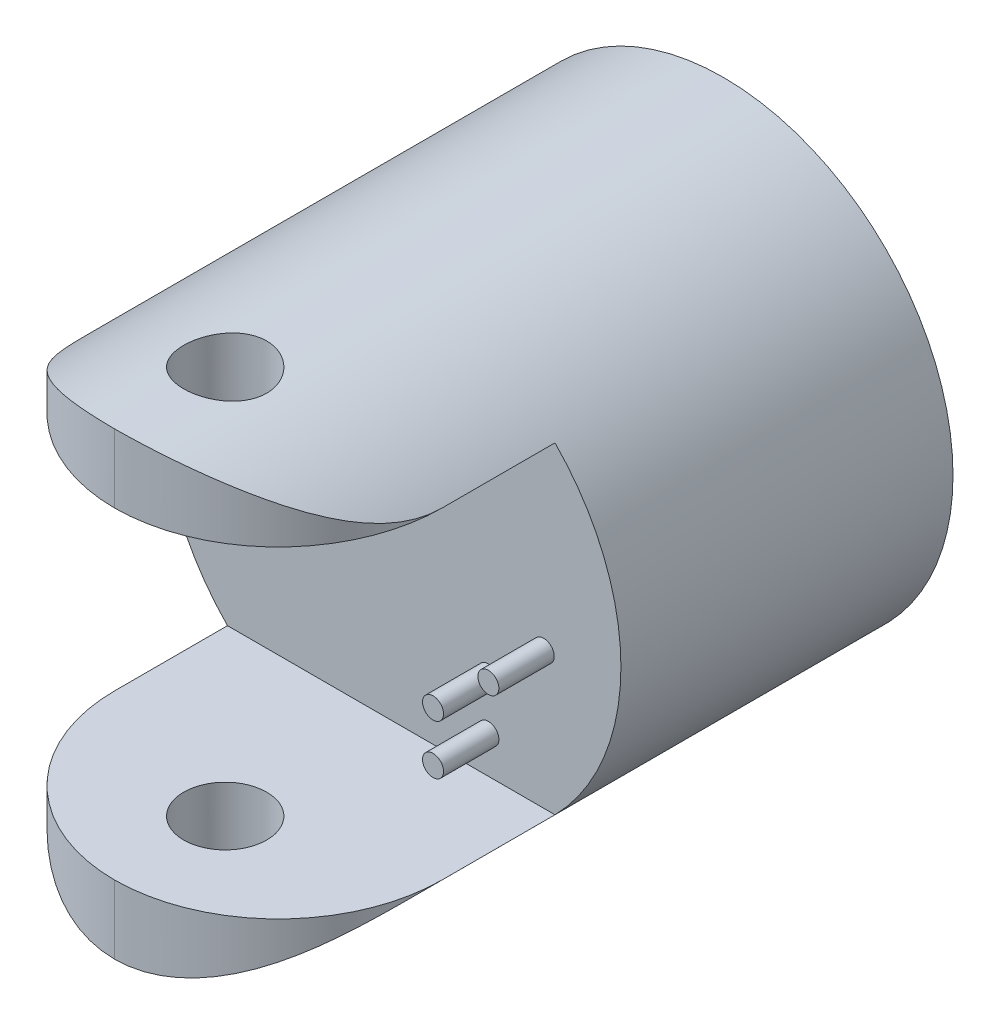
SolidWorks part; units mm, degrees
ref_plane "Front Plane" through (0, 0, 0) normal (0, 0, 1) x (1, 0, 0)
ref_plane "Top Plane" through (0, 0, 0) normal (0, 1, 0) x (1, 0, 0)
ref_plane "Right Plane" through (0, 0, 0) normal (1, 0, 0) x (0, 0, -1)
sketch "Sketch1" plane through (0, 0, 0) normal (0, 0, 1) x (1, 0, 0)
  circle A0 centre (0, 0) radius 4.15
extrude "Boss-Extrude1" add sketch "Sketch1" along normal blind 11
sketch "Sketch2" plane through (0, 0, 11) normal (0, 0, 1) x (1, 0, 0)
  line L1 (-4.1876, 2.91) -> (4.1876, 2.91)
  line L2 (-4.1876, 2.91) -> (-4.1876, -2.91)
  line L3 (-4.1876, -2.91) -> (4.1876, -2.91)
  line L4 (4.1876, 2.91) -> (4.1876, -2.91)
  line L5 (-4.1876, 2.91) -> (4.1876, -2.91) construction
  line L6 (-4.1876, -2.91) -> (4.1876, 2.91) construction
  point P0 (0, 0)
  dimension "D1" = 4.1876
  dimension "D2" = 5.82
extrude "Cut-Extrude1" cut sketch "Sketch2" against normal blind 5
sketch "Sketch3" plane through (0, 0, 0) normal (0, 1, 0) x (1, 0, 0)
  line L2 (-2.9588, -8.0314) -> (-2.9588, -11)
  line L3 (-2.9588, -11) -> (0, -11)
  arc A1 (-2.9588, -8.0314) -> (0, -11) centre (0.0098, -8.0314) ccw
extrude "Cut-Extrude2" cut sketch "Sketch3" against normal through all both and the other way through all
mirror "Mirror1" about plane through (0, 0, 0) normal (1, 0, 0) of "Cut-Extrude2"
sketch "Sketch4" plane through (0, 0, 0) normal (0, 1, 0) x (1, 0, 0)
  line L0 (0, 0) -> (0, -9) construction
  circle A0 centre (0, -9) radius 0.75
extrude "Cut-Extrude3" cut sketch "Sketch4" against normal through all both and the other way through all
sketch "Sketch5" plane through (0, 0, 6) normal (0, 0, 1) x (1, 0, 0)
  line L8 (2.755, -0.25) -> (2.755, -0.44) construction
  circle A17 centre (-1.755, 2.26) radius 0.19
  circle A18 centre (-1.755, 1.36) radius 0.19
  circle A23 centre (1.755, -1.34) radius 0.19
  circle A24 centre (1.755, -2.24) radius 0.19
  circle A25 centre (-2.755, 0.46) radius 0.19
  circle A28 centre (2.755, -0.44) radius 0.19
extrude "Boss-Extrude2" add sketch "Sketch5" along normal blind 1
